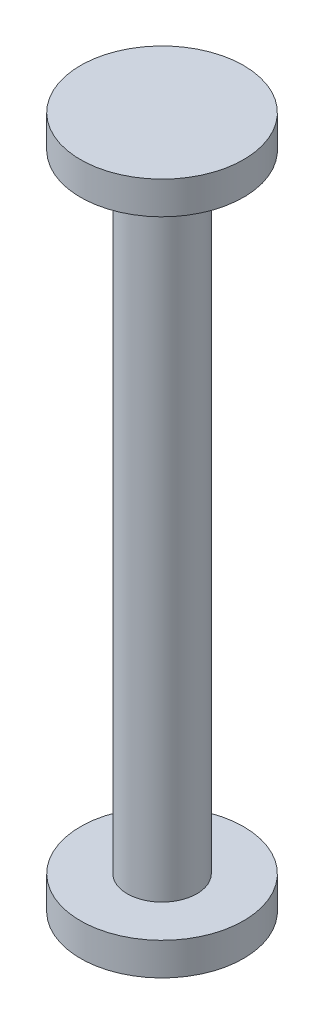
SolidWorks part; units mm, degrees
ref_plane "Front Plane" through (0, 0, 0) normal (0, 0, 1) x (1, 0, 0)
ref_plane "Top Plane" through (0, 0, 0) normal (0, 1, 0) x (1, 0, 0)
ref_plane "Right Plane" through (0, 0, 0) normal (1, 0, 0) x (0, 0, -1)
sketch "Sketch1" plane through (0, 0, 0) normal (0, 1, 0) x (1, 0, 0)
  circle A0 centre (0, 0) radius 9.525
  dimension "D1" = 19.05
extrude "Boss-Extrude1" add sketch "Sketch1" along normal blind 3.81
sketch "Sketch2" plane through (0, 3.81, 0) normal (0, 1, 0) x (1, 0, 0)
  circle A0 centre (0, 0) radius 4.064
  dimension "D1" = 8.128
extrude "Boss-Extrude2" add sketch "Sketch2" along normal blind 73.152
sketch "Sketch3" plane through (0, 76.962, 0) normal (0, 1, 0) x (1, 0, 0)
  circle A0 centre (0, 0) radius 9.525
extrude "Boss-Extrude3" add sketch "Sketch3" along normal blind 3.81
